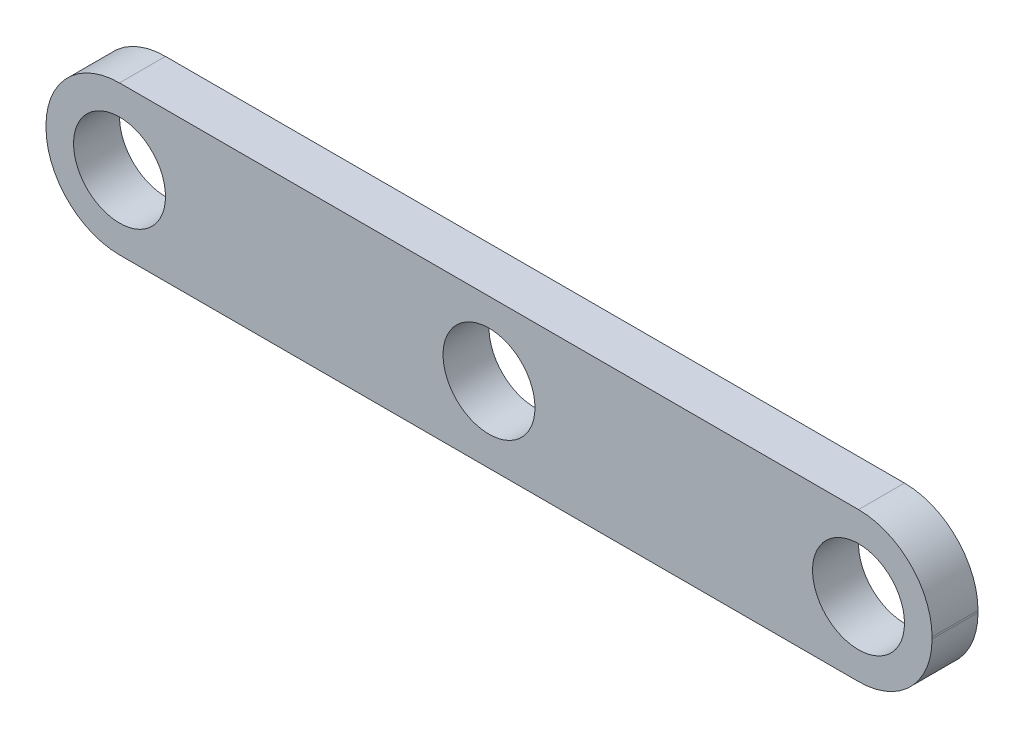
SolidWorks part; units mm, degrees
ref_plane "Front Plane" through (0, 0, 0) normal (0, 0, 1) x (1, 0, 0)
ref_plane "Top Plane" through (0, 0, 0) normal (0, 1, 0) x (1, 0, 0)
ref_plane "Right Plane" through (0, 0, 0) normal (1, 0, 0) x (0, 0, -1)
sketch "Sketch1" plane through (0, 0, 0) normal (0, 0, 1) x (1, 0, 0)
  line L0 (-96.7735, -21.1882) -> (96.0322, -21.1882) construction
  line L1 (-80.7735, -5.1882) -> (80.0322, -5.1882)
  line L2 (-96.7735, -21.1882) -> (-96.7735, -21.6069)
  line L3 (-80.7735, -37.6069) -> (80.0322, -37.6069)
  line L4 (96.0322, -21.1882) -> (96.0322, -21.6069)
  circle A0 centre (-80.7735, -21.6069) radius 10
  arc A1 (-96.7735, -21.6069) -> (-80.7735, -37.6069) centre (-80.7735, -21.6069) ccw
  arc A2 (-80.7735, -5.1882) -> (-96.7735, -21.1882) centre (-80.7735, -21.1882) ccw
  arc A3 (80.0322, -37.6069) -> (96.0322, -21.6069) centre (80.0322, -21.6069) ccw
  arc A4 (80.0322, -5.1882) -> (96.0322, -21.1882) centre (80.0322, -21.1882) cw
  circle A5 centre (80.0322, -21.6069) radius 10
  circle A6 centre (-0.3706, -21.1882) radius 10
  point P15 (-76.2357, -16.6045)
  point P17 (-0.3706, -21.1882)
  dimension "D1" = 16
  dimension "D2" = 16
extrude "Boss-Extrude1" add sketch "Sketch1" along normal blind 10
